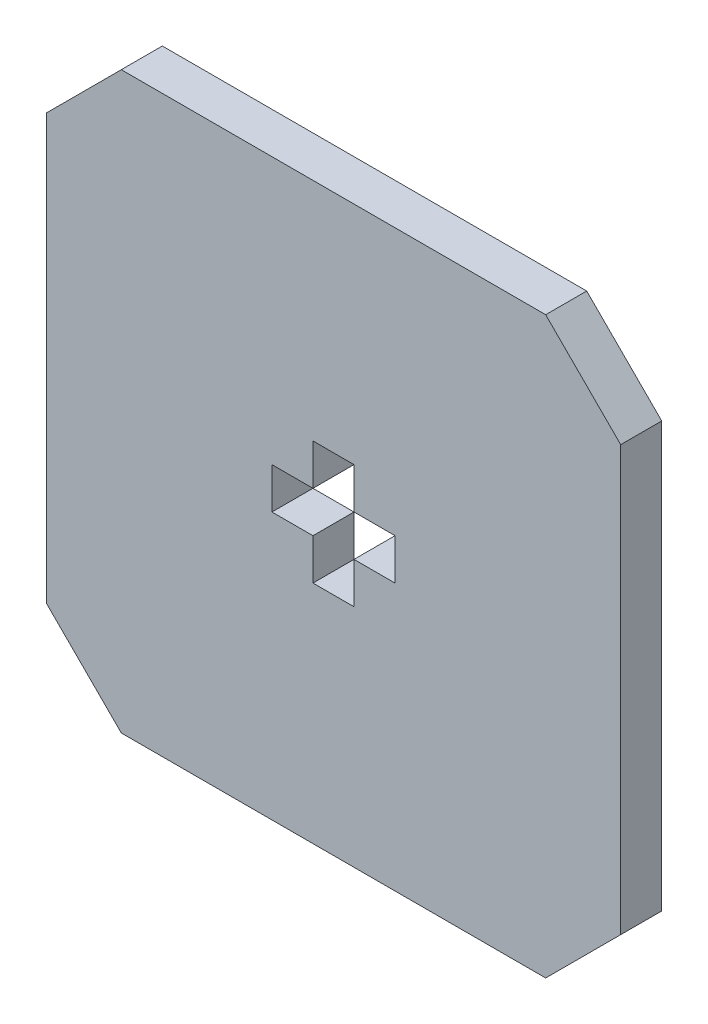
SolidWorks part; units mm, degrees
ref_plane "Front Plane" through (0, 0, 0) normal (0, 0, 1) x (1, 0, 0)
ref_plane "Top Plane" through (0, 0, 0) normal (0, 1, 0) x (1, 0, 0)
ref_plane "Right Plane" through (0, 0, 0) normal (1, 0, 0) x (0, 0, -1)
sketch "Sketch1" plane through (0, 0, 0) normal (0, 0, 1) x (1, 0, 0)
  line L1045 (412.5, 280.5) -> (412.5, 277.5)
  line L1046 (412.5, 277.5) -> (415.5, 277.5)
  line L1047 (415.5, 277.5) -> (415.5, 274.5)
  line L1048 (415.5, 274.5) -> (412.5, 274.5)
  line L1049 (412.5, 274.5) -> (412.5, 271.5)
  line L1050 (412.5, 271.5) -> (409.5, 271.5)
  line L1051 (409.5, 271.5) -> (409.5, 274.5)
  line L1052 (409.5, 274.5) -> (406.5, 274.5)
  line L1053 (406.5, 274.5) -> (406.5, 277.5)
  line L1054 (406.5, 277.5) -> (409.5, 277.5)
  line L1055 (409.5, 277.5) -> (409.5, 280.5)
  line L1056 (409.5, 280.5) -> (412.5, 280.5)
  line L1057 (426.5147, 255) -> (395.4853, 255)
  line L1058 (395.4853, 255) -> (390, 260.4853)
  line L1059 (390, 260.4853) -> (390, 291.5147)
  line L1060 (390, 291.5147) -> (395.4853, 297)
  line L1061 (395.4853, 297) -> (426.5147, 297)
  line L1062 (426.5147, 297) -> (432, 291.5147)
  line L1063 (432, 291.5147) -> (432, 260.4853)
  line L1064 (432, 260.4853) -> (426.5147, 255)
extrude "Boss-Extrude1" add sketch "Sketch1" along normal blind 3
